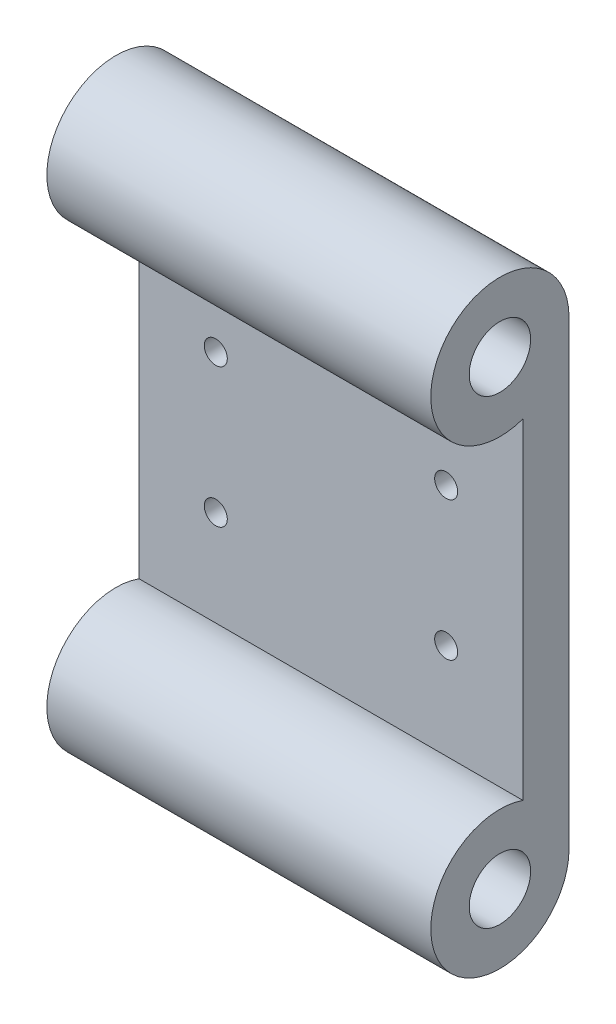
SolidWorks part; units mm, degrees
material "ABS"
ref_plane "Plano frontal" through (0, 0, 0) normal (0, 0, 1) x (1, 0, 0)
ref_plane "Plano superior" through (0, 0, 0) normal (0, 1, 0) x (1, 0, 0)
ref_plane "Plano direito" through (0, 0, 0) normal (1, 0, 0) x (0, 0, -1)
sketch "Esboço2" plane through (0, 0, 0) normal (1, 0, 0) x (0, 0, -1)
  line L0 (0, 30) -> (0, -30) construction
  line L1 (9, 30) -> (9, -30)
  line L2 (3, -21.5147) -> (3, 21.5147)
  circle A0 centre (0, 30) radius 4
  arc A1 (9, 30) -> (3, 21.5147) centre (0, 30) ccw
  arc A2 (3, -21.5147) -> (9, -30) centre (0, -30) ccw
  circle A3 centre (0, -30) radius 4
  circle A4 centre (0, 30) radius 4 construction
  circle A5 centre (0, -30) radius 4 construction
  point P8 (0, 0)
  dimension "D1" = 8
  dimension "D2" = 8
  dimension "D3" = 18
  dimension "D4" = 60
  dimension "D5" = 6
extrude "Ressalto-extrusão1" add sketch "Esboço2" along normal blind 50
sketch "Esboço5" plane through (0, 0, -3) normal (0, 0, 1) x (1, 0, 0)
  line L0 (50, 0) -> (0, 0) construction
  line L1 (50, 21.5147) -> (50, -21.5147) construction
  line L9 (10, -9.0444) -> (10, 9.0444) construction
  line L10 (0, 21.5147) -> (0, -21.5147) construction
  line L12 (40, -9.0444) -> (40, 9.0444) construction
  circle A5 centre (10, 9.0444) radius 1.5
  circle A6 centre (40, 9.0444) radius 1.5
  circle A7 centre (40, -9.0444) radius 1.5
  circle A8 centre (10, -9.0444) radius 1.5
  point P18 (25, 0)
  point P20 (10, 0)
  point P25 (40, 0)
  point P28 (25, 0)
  dimension "D5" = 3
  dimension "D7" = 10
  dimension "D8" = 30
extrude "Corte-extrusão2" cut sketch "Esboço5" against normal blind 40
sketch "Esboço6" plane through (0, 0, -9) normal (0, 0, -1) x (-1, 0, 0)
  line L0 (-25, 39) -> (-25, 21) construction
  line L1 (0, 39) -> (-50, 39) construction
  line L2 (-35, 21) -> (-15, 21)
  line L3 (0, 39) -> (-50, 39) construction
  line L4 (-35, 39) -> (-15, 39)
  line L5 (-15, 21) -> (-15, 39)
  line L7 (-35, 39) -> (-35, 21)
  line L8 (0, 0) -> (-50, 0) construction
  line L9 (-50, -30) -> (-50, 30) construction
  line L10 (-25, -39) -> (-25, -21) construction
  line L11 (-35, -39) -> (-35, -21)
  line L12 (-15, -21) -> (-15, -39)
  line L13 (-35, -39) -> (-15, -39)
  line L14 (-35, -21) -> (-15, -21)
  line L15 (-50, 21) -> (0, 21) construction
  line L17 (-50, 21) -> (0, 21) construction
  point P11 (-25, 21)
  point P13 (-24.9847, 25.3156)
  point P14 (-25, 39)
  point P15 (-24.9059, 19.9406)
  point P18 (-24.9554, 25.2876)
  point P26 (-25, 30)
  point P29 (-25, 21)
  dimension "D1" = 20
  dimension "D2" = 90
extrude "Corte-extrusão3" [suppressed] cut sketch "Esboço6" against normal through all
